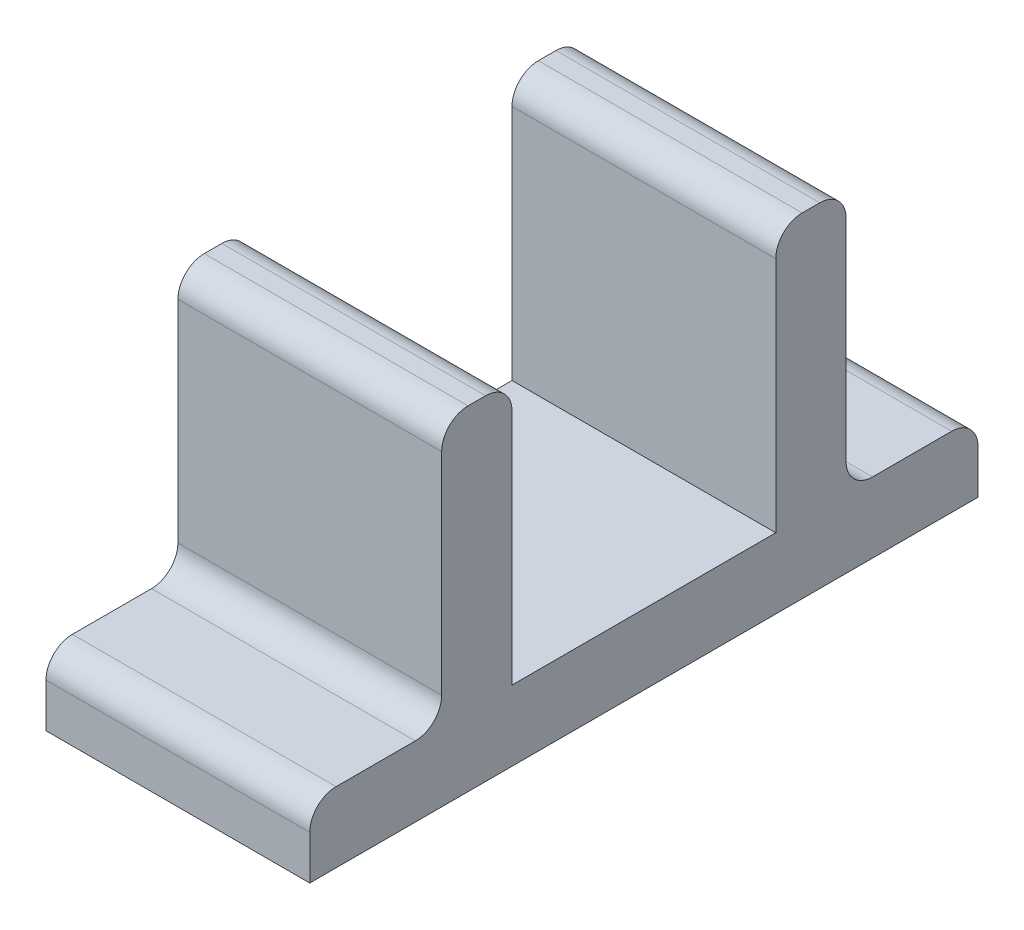
SolidWorks part; units mm, degrees
ref_plane "Front Plane" through (0, 0, 0) normal (0, 0, 1) x (1, 0, 0)
ref_plane "Top Plane" through (0, 0, 0) normal (0, 1, 0) x (1, 0, 0)
ref_plane "Right Plane" through (0, 0, 0) normal (1, 0, 0) x (0, 0, -1)
sketch "Sketch1" plane through (0, 0, 0) normal (1, 0, 0) x (0, 0, -1)
  line L0 (0, 8) -> (0, 38)
  line L1 (0, 38) -> (8, 38)
  line L2 (8, 38) -> (8, 8)
  line L3 (8, 8) -> (38, 8)
  line L4 (38, 8) -> (38, 38)
  line L5 (38, 38) -> (46, 38)
  line L6 (46, 8) -> (46, 38)
  line L7 (-15, 0) -> (61, 0)
  line L9 (-15, 0) -> (-15, 8)
  line L10 (-15, 8) -> (0, 8)
  line L12 (46, 8) -> (61, 8)
  line L13 (61, 8) -> (61, 0)
  line L15 (46, 0) -> (46.0743, 0.092)
  dimension "D1" = 30
  dimension "D2" = 8
  dimension "D3" = 30
  dimension "D5" = 15
extrude "Boss-Extrude2" add sketch "Sketch1" along normal blind 30
fillet "Fillet1" radius 3 8 edges at (15, 8, -61) (15, 8, -46) (15, 8, 0) (15, 8, 15) (15, 38, -46) (15, 38, 0) (15, 38, -38) (15, 38, -8)
